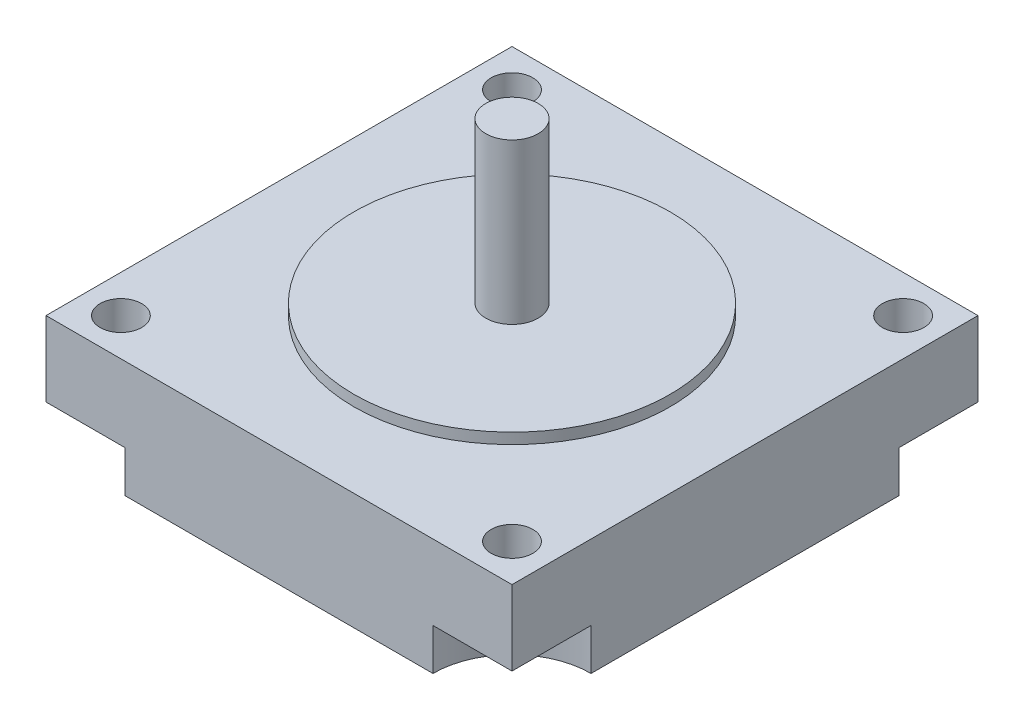
SolidWorks part; units mm, degrees
material "1060 Alloy"
ref_plane "Front Plane" through (0, 0, 0) normal (0, 0, 1) x (1, 0, 0)
ref_plane "Top Plane" through (0, 0, 0) normal (0, 1, 0) x (1, 0, 0)
ref_plane "Right Plane" through (0, 0, 0) normal (1, 0, 0) x (0, 0, -1)
sketch "Sketch1" plane through (0, 0, 0) normal (0, 1, 0) x (1, 0, 0)
  line L1 (-18.5, 28) -> (18.5, 28)
  line L2 (-28, 18.5) -> (-28, -18.5)
  line L3 (-18.5, -28) -> (18.5, -28)
  line L4 (28, 18.5) -> (28, -18.5)
  line L5 (-21.2825, 21.2825) -> (21.2825, -21.2825) construction
  line L6 (-21.2825, -21.2825) -> (21.2825, 21.2825) construction
  arc A0 (-28, 18.5) -> (-18.5, 28) centre (-28, 28) ccw
  arc A1 (18.5, 28) -> (28, 18.5) centre (28, 28) ccw
  arc A2 (28, -18.5) -> (18.5, -28) centre (28, -28) ccw
  arc A3 (-18.5, -28) -> (-28, -18.5) centre (-28, -28) ccw
  point P0 (0, 0)
  dimension "D3" = 19
  dimension "D1" = 56
  dimension "D2" = 56
extrude "Boss-Extrude5" add sketch "Sketch1" along normal blind 5
sketch "Sketch6" plane through (0, 5, 0) normal (0, 1, 0) x (1, 0, 0)
  line L1 (-28, 28) -> (28, 28)
  line L2 (-28, 28) -> (-28, -28)
  line L3 (-28, -28) -> (28, -28)
  line L4 (28, 28) -> (28, -28)
  line L5 (-28, 28) -> (28, -28) construction
  line L6 (-28, -28) -> (28, 28) construction
  point P0 (0, 0)
  dimension "D1" = 56
  dimension "D2" = 56
extrude "Boss-Extrude6" add sketch "Sketch6" along normal blind 9
sketch "Sketch7" plane through (0, 14, 0) normal (0, 1, 0) x (1, 0, 0)
  circle A0 centre (0, 0) radius 19
  dimension "D1" = 38
extrude "Boss-Extrude7" add sketch "Sketch7" along normal blind 1.3
sketch "Sketch8" plane through (0, 14, 0) normal (0, 1, 0) x (1, 0, 0)
  circle A0 centre (-23.5, 23.5) radius 2.5
  circle A1 centre (23.5, 23.5) radius 2.5
  circle A2 centre (23.5, -23.5) radius 2.5
  circle A3 centre (-23.5, -23.5) radius 2.5
  point P0 (0, 0)
  dimension "D3" = 5
  dimension "D1" = 47
  dimension "D2" = 47
extrude "Cut-Extrude1" cut sketch "Sketch8" against normal through all
sketch "Sketch9" plane through (0, 15.3, 0) normal (0, 1, 0) x (1, 0, 0)
  circle A0 centre (0, 0) radius 3.15
  dimension "D1" = 6.3
extrude "Boss-Extrude8" add sketch "Sketch9" along normal blind 19.2
